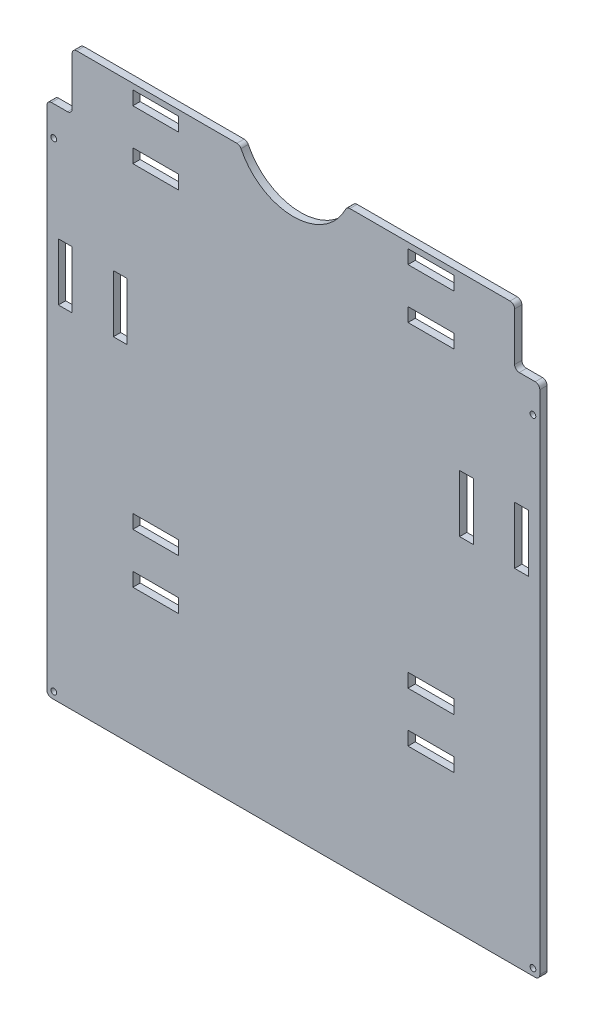
SolidWorks part; units mm, degrees
ref_plane "Front Plane" through (0, 0, 0) normal (0, 0, 1) x (1, 0, 0)
ref_plane "Top Plane" through (0, 0, 0) normal (0, 1, 0) x (1, 0, 0)
ref_plane "Right Plane" through (0, 0, 0) normal (1, 0, 0) x (0, 0, -1)
sketch "Sketch1" plane through (0, 0, 0) normal (0, 0, 1) x (1, 0, 0)
  line L1 (-107.5, -125) -> (107.5, -125)
  line L2 (-107.5, -125) -> (-107.5, 125)
  line L3 (-107.5, 125) -> (107.5, 125)
  line L4 (107.5, -125) -> (107.5, 125)
  line L5 (-107.5, -125) -> (107.5, 125) construction
  line L6 (-107.5, 125) -> (107.5, -125) construction
  point P0 (0, 0)
  dimension "D1" = 215
  dimension "D2" = 250
extrude "Boss-Extrude1" add sketch "Sketch1" along normal blind 3.175
sketch "Sketch2" plane through (0, 0, 3.175) normal (0, 0, 1) x (1, 0, 0)
  line L0 (107.5, -125) -> (107.5, 125) construction
  line L1 (107.5, 125) -> (-107.5, 125) construction
  circle A0 centre (0, 135) radius 25.4
  dimension "D3" = 50.8
  dimension "D1" = 107.5
  dimension "D2" = 10
extrude "Cut-Extrude1" cut sketch "Sketch2" against normal through all
sketch "Sketch3" plane through (0, 0, 3.175) normal (0, 0, 1) x (1, 0, 0)
  line L1 (-107.5, 125) -> (-96.5, 125)
  line L2 (-107.5, 125) -> (-107.5, 100)
  line L3 (-107.5, 100) -> (-96.5, 100)
  line L4 (-96.5, 125) -> (-96.5, 100)
  dimension "D1" = 11
  dimension "D2" = 25
extrude "Cut-Extrude2" cut sketch "Sketch3" against normal through all
mirror "Mirror1" about plane through (0, 0, 0) normal (1, 0, 0) of "Cut-Extrude2"
fillet "Fillet1" radius 2 10 edges at (107.5, 100, 1.5875) (107.5, -125, 1.5875) (-107.5, -125, 1.5875) (-107.5, 100, 1.5875) (-96.5, 100, 1.5875) (-23.3487, 125, 1.5875) (23.3487, 125, 1.5875) (96.5, 125, 1.5875) (96.5, 100, 1.5875) (-96.5, 125, 1.5875)
sketch "Sketch4" plane through (0, 0, 0) normal (0, 0, -1) x (-1, 0, 0)
  line L1 (-70, -43.5) -> (-50, -43.5)
  line L2 (-70, -43.5) -> (-70, -37.5)
  line L3 (-70, -37.5) -> (-50, -37.5)
  line L4 (-50, -43.5) -> (-50, -37.5)
  line L5 (-70, -59.375) -> (-50, -59.375)
  line L6 (-70, -59.375) -> (-70, -65.375)
  line L7 (-70, -65.375) -> (-50, -65.375)
  line L8 (-50, -59.375) -> (-50, -65.375)
  dimension "D1" = 6
  dimension "D2" = 15.875
  dimension "D3" = 43.5
  dimension "D4" = 50
  dimension "D5" = 20
extrude "Cut-Extrude3" cut sketch "Sketch4" against normal through all
mirror "Mirror2" about plane through (0, 0, 0) normal (1, 0, 0) of "Cut-Extrude3"
pattern_linear "LPattern1" count 2 spacing 160 along (0, 1, 0) of "Cut-Extrude3", "Mirror2"
sketch "Sketch5" plane through (0, 0, 3.175) normal (0, 0, 1) x (1, 0, 0)
  line L0 (-105.5, -125) -> (105.5, -125) construction
  line L1 (-104.5, -122) -> (104.5, -122) construction
  line L2 (-104.5, -122) -> (-104.5, 87) construction
  line L3 (-104.5, 87) -> (104.5, 87) construction
  line L4 (104.5, -122) -> (104.5, 87) construction
  line L5 (-107.5, 98) -> (-107.5, -123) construction
  circle A0 centre (-104.5, 87) radius 1.5
  circle A1 centre (104.5, 87) radius 1.5
  circle A2 centre (104.5, -122) radius 1.5
  circle A3 centre (-104.5, -122) radius 1.5
  dimension "D5" = 3
  dimension "D1" = 3
  dimension "D2" = 3
  dimension "D3" = 209
  dimension "D4" = 209
hole_wizard "M3x0.5 Tapped Hole1" positions "Sketch7" profile "Sketch8" tap size "M3x0.5" standard "ANSI Metric" end condition through all
sketch "Sketch7" plane through (0, 0, 0) normal (0, 0, -1) x (-1, 0, 0)
  point P0 (-104.5, 87)
  point P3 (104.5, 87)
  point P6 (104.5, -122)
  point P9 (-104.5, -122)
sketch "Sketch8" plane through (104.5, 87, 0) normal (1, 0, 0) x (0, 1, 0)
  line L0 (0, 0) -> (0, 3.175)
  line L1 (0, 3.175) -> (1.25, 3.175)
  line L2 (1.25, 3.175) -> (1.25, 0)
  line L5 (1.25, 0) -> (0, 0)
  line L11 (0, -6.35) -> (0, 107.95) construction
  dimension "Thread Major Dia." = 2.5
  dimension "Thru Tap Drill Depth" = 3.175
sketch "Sketch9" plane through (0, 0, 0) normal (0, 0, -1) x (-1, 0, 0)
  line L0 (78.5, 100.753) -> (78.5, -43.753) construction
  line L1 (72.5, 50) -> (78.5, 50)
  line L2 (72.5, 50) -> (72.5, 25)
  line L3 (72.5, 25) -> (78.5, 25)
  line L4 (78.5, 50) -> (78.5, 25)
  line L5 (96.5, 100.753) -> (96.5, -43.753) construction
  line L6 (96.5, 50) -> (102.5, 50)
  line L7 (96.5, 50) -> (96.5, 25)
  line L8 (96.5, 25) -> (102.5, 25)
  line L9 (102.5, 50) -> (102.5, 25)
  dimension "D1" = 25
  dimension "D2" = 6
  dimension "D3" = 50
extrude "Cut-Extrude4" cut sketch "Sketch9" against normal through all
mirror "Mirror3" about plane through (0, 0, 0) normal (1, 0, 0) of "Cut-Extrude4"
sketch "Sketch10" plane through (0, 0, 0) normal (0, 0, -1) x (-1, 0, 0)
  line L5 (-102.5, 37.5) -> (-96.5, 37.5) construction
  line L6 (-102.5, 25) -> (-102.5, 50) construction
  line L7 (-96.5, 50) -> (-96.5, 25) construction
  line L12 (-78.5, 37.5) -> (-72.5, 37.5) construction
  line L13 (-78.5, 25) -> (-78.5, 50) construction
  line L14 (-72.5, 50) -> (-72.5, 25) construction
  line L15 (-60, 122.5) -> (-60, 116.5) construction
  line L16 (-50, 122.5) -> (-70, 122.5) construction
  line L17 (-70, 116.5) -> (-50, 116.5) construction
  line L18 (-60, 100.625) -> (-60, 94.625) construction
  line L19 (-50, 100.625) -> (-70, 100.625) construction
  line L20 (-70, 94.625) -> (-50, 94.625) construction
  line L21 (60, 122.5) -> (60, 116.5) construction
  line L22 (50, 122.5) -> (70, 122.5) construction
  line L23 (70, 116.5) -> (50, 116.5) construction
  line L24 (60, 100.625) -> (60, 94.625) construction
  line L25 (50, 100.625) -> (70, 100.625) construction
  line L26 (70, 94.625) -> (50, 94.625) construction
  line L27 (72.5, 37.5) -> (78.5, 37.5) construction
  line L28 (72.5, 50) -> (72.5, 25) construction
  line L29 (78.5, 25) -> (78.5, 50) construction
  line L30 (96.5, 37.5) -> (102.5, 37.5) construction
  line L31 (96.5, 50) -> (96.5, 25) construction
  line L32 (102.5, 25) -> (102.5, 50) construction
  line L33 (60, -37.5) -> (60, -43.5) construction
  line L34 (50, -37.5) -> (70, -37.5) construction
  line L35 (70, -43.5) -> (50, -43.5) construction
  line L36 (60, -59.375) -> (60, -65.375) construction
  line L37 (50, -59.375) -> (70, -59.375) construction
  line L38 (70, -65.375) -> (50, -65.375) construction
  line L39 (-60, -59.375) -> (-60, -65.375) construction
  line L40 (-50, -59.375) -> (-70, -59.375) construction
  line L41 (-70, -65.375) -> (-50, -65.375) construction
  line L42 (-60, -37.5) -> (-60, -43.5) construction
  line L43 (-50, -37.5) -> (-70, -37.5) construction
  line L44 (-70, -43.5) -> (-50, -43.5) construction
  circle A0 centre (-99.5, 37.5) radius 3
  circle A1 centre (-75.5, 37.5) radius 3
  circle A2 centre (-60, 97.625) radius 3
  circle A3 centre (-60, 119.5) radius 3
  circle A4 centre (60, 119.5) radius 3
  circle A5 centre (60, 97.625) radius 3
  circle A6 centre (75.5, 37.5) radius 3
  circle A7 centre (99.5, 37.5) radius 3
  circle A8 centre (60, -40.5) radius 3
  circle A9 centre (60, -62.375) radius 3
  circle A10 centre (-60, -62.375) radius 3
  circle A11 centre (-60, -40.5) radius 3
  dimension "D1" = 6
